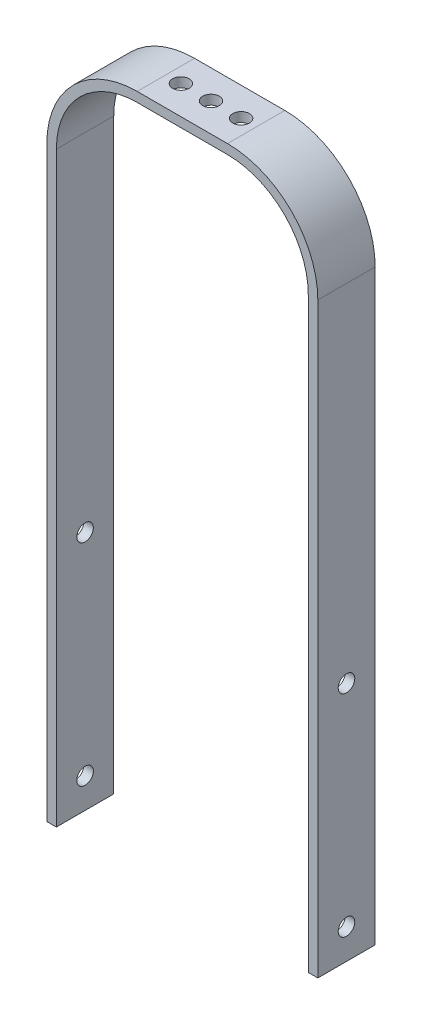
SolidWorks part; units mm, degrees
ref_plane "Front Plane" through (0, 0, 0) normal (0, 0, 1) x (1, 0, 0)
ref_plane "Top Plane" through (0, 0, 0) normal (0, 1, 0) x (1, 0, 0)
ref_plane "Right Plane" through (0, 0, 0) normal (1, 0, 0) x (0, 0, -1)
sketch "Sketch1" plane through (0, 0, 0) normal (0, 0, 1) x (1, 0, 0)
  line L0 (45, 45) -> (45, 240)
  line L1 (0, 0) -> (0, 109.6692) construction
  line L2 (41.825, 240) -> (41.825, 45)
  line L3 (-45, 45) -> (-41.825, 45)
  line L4 (15, 270) -> (-15, 270)
  line L5 (41.825, 45) -> (45, 45)
  line L6 (-15, 266.825) -> (15, 266.825)
  line L8 (-41.825, 240) -> (-41.825, 45)
  line L9 (-45, 45) -> (-45, 240)
  arc A0 (45, 240) -> (15, 270) centre (15, 240) ccw
  arc A1 (15, 266.825) -> (41.825, 240) centre (15, 240) cw
  arc A2 (-15, 266.825) -> (-41.825, 240) centre (-15, 240) ccw
  arc A3 (-45, 240) -> (-15, 270) centre (-15, 240) cw
  dimension "D4" = 30
  dimension "D5" = 45
  dimension "D6" = 3.175
  dimension "D1" = 270
  dimension "D2" = 41.825
  dimension "D3" = 30
extrude "Boss-Extrude1" add sketch "Sketch1" along normal mid plane 19.05
sketch "Sketch12" plane through (0, 270, 0) normal (0, 1, 0) x (1, 0, 0)
  line L0 (-15, -9.525) -> (-15, 9.525) construction
  line L1 (15, -9.525) -> (15, 9.525) construction
  circle A0 centre (0, 0) radius 2.75
  circle A1 centre (-10, 0) radius 2.75
  circle A2 centre (10, 0) radius 2.75
  dimension "D1" = 5.5
  dimension "D2" = 5
  dimension "D3" = 5
extrude "Cut-Extrude2" cut sketch "Sketch12" against normal through all
sketch "Sketch13" plane through (45, 0, 0) normal (1, 0, 0) x (0, 0, -1)
  line L0 (0, 0) -> (0, 240) construction
  line L1 (-9.525, 240) -> (9.525, 240) construction
  circle A1 centre (0, 125) radius 2.75
  circle A2 centre (0, 55) radius 2.75
  dimension "D1" = 115
  dimension "D2" = 5.5
  dimension "D3" = 70
extrude "Cut-Extrude3" cut sketch "Sketch13" against normal through all both and the other way through all
sketch "Sketch15" plane through (45, 0, 0) normal (1, 0, 0) x (0, 0, -1)
  line L0 (-9.525, 240) -> (9.525, 240) construction
  circle A0 centre (0, 234.35) radius 5
  dimension "D1" = 10
  dimension "D2" = 5.65
